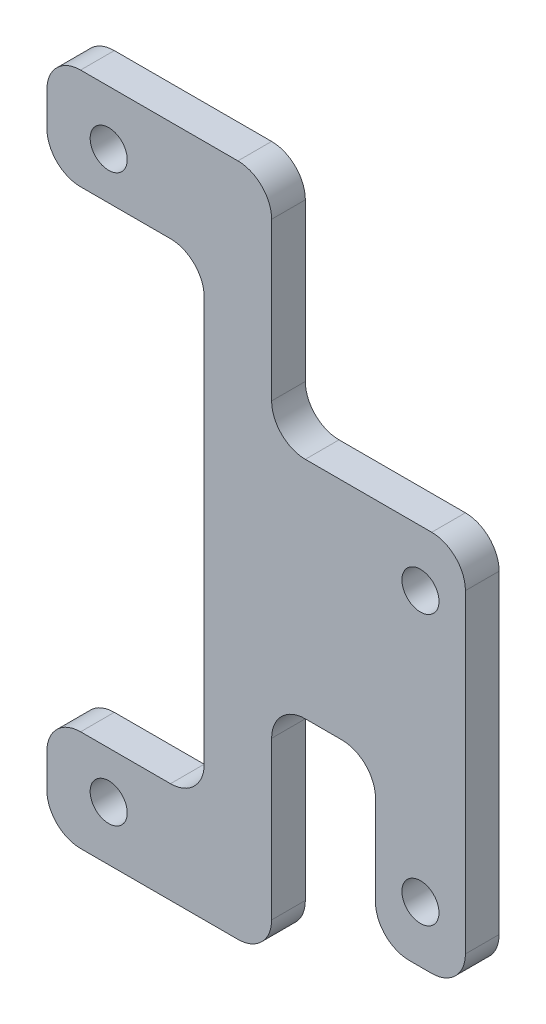
SolidWorks part; units mm, degrees
ref_plane "Front Plane" through (0, 0, 0) normal (0, 0, 1) x (1, 0, 0)
ref_plane "Top Plane" through (0, 0, 0) normal (0, 1, 0) x (1, 0, 0)
ref_plane "Right Plane" through (0, 0, 0) normal (1, 0, 0) x (0, 0, -1)
sketch "Sketch1" plane through (0, 0, 0) normal (0, 0, 1) x (1, 0, 0)
  line L8 (-35.3845, 0) -> (43.3618, 0) construction
  line L9 (-4, 17) -> (4, 17)
  line L10 (-4, 17) -> (-4, -17)
  line L11 (-4, -17) -> (4, -17)
  line L12 (4, 17) -> (4, -17)
  line L13 (-4, 17) -> (4, -17) construction
  line L14 (-4, -17) -> (4, 17) construction
  line L15 (0, 28.0694) -> (0, -29.0843) construction
  line L16 (-22.9881, 12) -> (22.2389, 12) construction
  line L17 (-22.9881, -12) -> (22.2389, -12) construction
  circle A3 centre (0, 12) radius 1.65
  circle A4 centre (0, -12) radius 1.65
  point P0 (0, 0)
  dimension "D1" = 34
  dimension "D2" = 8
  dimension "D4" = 3.3
  dimension "D3" = 24
extrude "Boss-Extrude1" add sketch "Sketch1" along normal blind 3
sketch "Sketch9" plane through (-4, 0, 0) normal (-1, 0, 0) x (0, 0, 1)
  line L0 (3, 17) -> (3, -17) construction
  line L1 (0, 17) -> (3, 17)
  line L2 (0, 17) -> (0, -3)
  line L3 (0, -3) -> (3, -3)
  line L4 (3, 17) -> (3, -3)
  dimension "D1" = 20
extrude "Boss-Extrude6" add sketch "Sketch9" along normal blind 9.245
sketch "Sketch10" plane through (-13.245, 0, 0) normal (-1, 0, 0) x (0, 0, 1)
  line L0 (-11.483, 7) -> (15.7939, 7) construction
  line L1 (1.5, 29.6966) -> (1.5, -10.5911) construction
  line L2 (3, -3) -> (3, -17) construction
  line L3 (0, 37) -> (3, 37)
  line L4 (0, 37) -> (0, -23)
  line L5 (0, -23) -> (3, -23)
  line L6 (3, 37) -> (3, -23)
  line L7 (0, 37) -> (3, -23) construction
  line L8 (0, -23) -> (3, 37) construction
  line L9 (3, 17) -> (0, 17) construction
  point P4 (1.5, 7)
  dimension "D1" = 60
  dimension "D2" = 10
extrude "Boss-Extrude7" add sketch "Sketch10" along normal blind 20
sketch "Sketch11" plane through (0, 0, 3) normal (0, 0, 1) x (1, 0, 0)
  line L0 (-43.3748, 7) -> (16.6147, 7) construction
  line L2 (-33.245, -23) -> (-33.245, 37) construction
  line L3 (-33.245, 28) -> (-19.245, 28)
  line L4 (-19.245, 28) -> (-19.245, -14)
  line L5 (-33.245, -14) -> (-19.245, -14)
  line L6 (-33.245, 28) -> (-33.245, -14)
  line L7 (-33.245, 37) -> (-13.245, 37) construction
  point P9 (-19.245, 7)
  dimension "D1" = 9
  dimension "D2" = 30
  dimension "D3" = 14
extrude "Cut-Extrude1" cut sketch "Sketch11" against normal blind 10
sketch "Sketch12" plane through (0, 0, 3) normal (0, 0, 1) x (1, 0, 0)
  line L0 (-39.8323, 32.17) -> (-1.7572, 32.17) construction
  line L1 (-50.954, 7) -> (15.1746, 7) construction
  line L2 (-27.745, 59.7378) -> (-27.745, 32.8332) construction
  line L3 (-33.245, 28) -> (-33.245, 37) construction
  line L4 (-27.745, -45.7378) -> (-27.745, -18.8332) construction
  line L5 (-39.8323, -18.17) -> (-1.7572, -18.17) construction
  line L8 (-19.245, 28) -> (-33.245, 28) construction
  circle A0 centre (-27.745, 32.17) radius 1.65
  circle A1 centre (-27.745, -18.17) radius 1.65
  dimension "D2" = 25.17
  dimension "D4" = 3.3
  dimension "D1" = 5.5
  dimension "D3" = 21
extrude "Cut-Extrude2" cut sketch "Sketch12" against normal blind 10
fillet "Fillet7" radius 3 14 edges at (4, -17, 1.5) (-4, -17, 1.5) (-4, -3, 1.5) (-13.245, -3, 1.5) (-13.245, -23, 1.5) (-33.245, -23, 1.5) (-33.245, -14, 1.5) (-19.245, -14, 1.5) (4, 17, 1.5) (-13.245, 17, 1.5) (-13.245, 37, 1.5) (-19.245, 28, 1.5) (-33.245, 28, 1.5) (-33.245, 37, 1.5)
